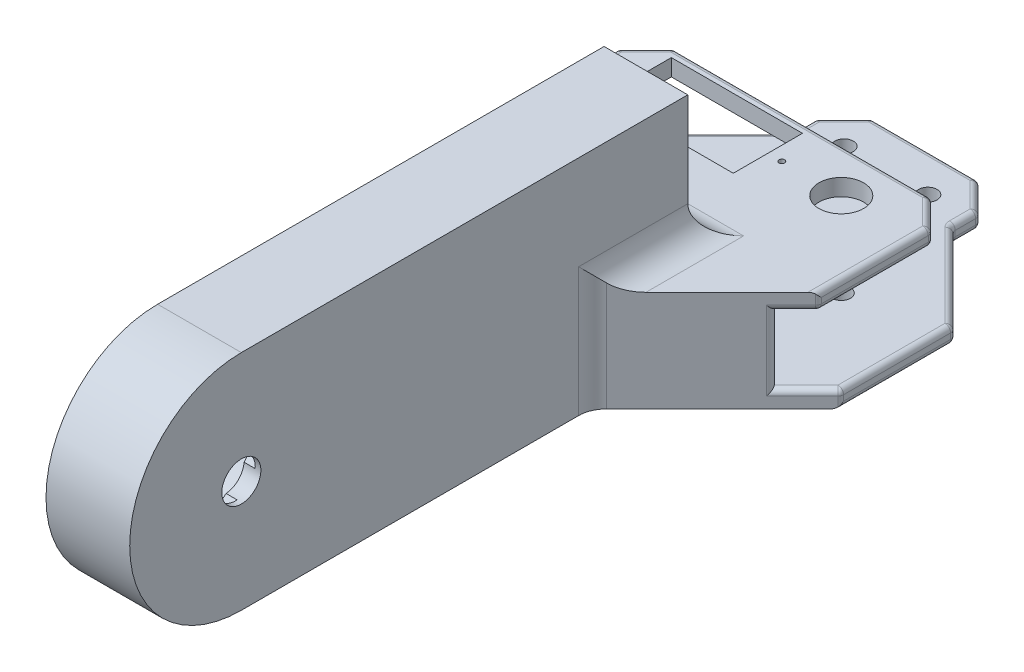
SolidWorks part; units mm, degrees
material "ABS"
ref_plane "Front Plane" through (0, 0, 0) normal (0, 0, 1) x (1, 0, 0)
ref_plane "Top Plane" through (0, 0, 0) normal (0, 1, 0) x (1, 0, 0)
ref_plane "Right Plane" through (0, 0, 0) normal (1, 0, 0) x (0, 0, -1)
sketch "Sketch1" plane through (0, 0, 0) normal (1, 0, 0) x (0, 0, -1)
  line L0 (0, 20) -> (80, 20)
  line L1 (0, -20) -> (80, -20)
  line L2 (80, 20) -> (80, -20)
  arc A0 (0, 20) -> (0, -20) centre (0, 0) ccw
  dimension "D1" = 40
  dimension "D2" = 80
  dimension "D3" = 80
extrude "Boss-Extrude1" add sketch "Sketch1" along normal blind 15
sketch "Sketch5" plane through (0, 0, 0) normal (-1, 0, 0) x (0, 0, 1)
  circle A0 centre (0, 0) radius 17
  arc A1 (0, -20) -> (0, 20) centre (0, 0) ccw construction
  dimension "D1" = 3
extrude "Cut-Extrude3" cut sketch "Sketch5" against normal offset from surface (12 mm away) 3 up to face at (15, 0, -35)
sketch "Sketch8" plane through (12, 0, 0) normal (-1, 0, 0) x (0, 0, 1)
  circle A0 centre (0, 0) radius 3.5
  dimension "D1" = 7
extrude "Cut-Extrude5" cut sketch "Sketch8" against normal up to surface (3 mm away) up to face at (15, 0, -35)
sketch "Sketch10" plane through (12, 0, 0) normal (-1, 0, 0) x (0, 0, 1)
  line L0 (-3.4905, -0.2571) -> (-11.7406, 8.915)
  line L1 (-8.915, 11.7406) -> (0.2571, 3.4905)
  line L2 (-2.4749, -2.4749) -> (2.4749, 2.4749) construction
  line L3 (0, -0.4614) -> (0, 0.843) construction
  line L6 (-10.253, 10.253) -> (2.4749, -2.4749) construction
  line L7 (11.7406, -8.915) -> (3.4905, 0.2571)
  line L8 (-0.2571, -3.4905) -> (8.915, -11.7406)
  arc A1 (-11.7406, 8.915) -> (-8.915, 11.7406) centre (-10.253, 10.253) cw
  circle A5 centre (0, 0) radius 3.5 construction
  arc A6 (-3.4885, -0.2839) -> (0.2571, 3.4905) centre (0, 0) cw
  arc A7 (-0.2839, -3.4885) -> (3.4905, 0.2571) centre (0, 0) ccw
  arc A8 (8.915, -11.7406) -> (11.7406, -8.915) centre (10.253, -10.253) ccw
  circle M6 centre (0, 0) radius 3.5
  dimension "D1" = 45
  dimension "D2" = 2.0008
  dimension "D5" = 90
  dimension "D3" = 5.3
  dimension "D4" = 18
extrude "Cut-Extrude8" cut sketch "Sketch10" against normal blind 2 contours A1 L0 L1 M6 | L8 A8 L7 M6
sketch "Sketch12" plane through (0, -20, 0) normal (0, -1, 0) x (1, 0, 0)
  line L0 (0, -80) -> (15, -80) construction
  line L1 (-17.5, -80) -> (32.5, -80)
  line L2 (32.5, -80) -> (37.5, -85)
  line L3 (37.5, -85) -> (37.5, -105)
  line L4 (37.5, -105) -> (22, -120.5)
  line L5 (22, -120.5) -> (22, -125)
  line L6 (22, -125) -> (17, -130)
  line L7 (17, -130) -> (-2, -130)
  line L8 (-2, -130) -> (-7, -125)
  line L9 (-7, -125) -> (-7, -120.5)
  line L10 (-7, -120.5) -> (-22.5, -105)
  line L12 (-22.5, -105) -> (-22.5, -85)
  line L13 (-22.5, -85) -> (-17.5, -80)
  line L14 (0, -80) -> (32.5, -80) construction
  line L15 (0, -70) -> (15, -70) construction
  line L16 (0, 0) -> (0, -80) construction
  line L17 (15, 0) -> (15, -80) construction
  line L18 (7.5, -80) -> (7.5, -70) construction
  line L19 (7.5, -130) -> (7.5, -80) construction
  line L20 (-22.5, -85) -> (37.5, -85) construction
  line L21 (-22.5, -105) -> (37.5, -105) construction
  line L22 (-7, -120.5) -> (22, -120.5) construction
  line L23 (-7, -125) -> (22, -125) construction
  dimension "D1" = 50
  dimension "D2" = 20
  dimension "D3" = 5
  dimension "D4" = 5
  dimension "D5" = 15.5
  dimension "D6" = 15.5
  dimension "D7" = 4.5
  dimension "D8" = 5
  dimension "D9" = 10
extrude "Boss-Extrude2" add sketch "Sketch12" against normal blind 3 separate body contours L12 L13 L1 L2 L3 L4 L5 L6 L7 L8 L9 L10
ref_plane "Plane1" through (0, -4.9, 0) normal (0, 1, 0) x (1, 0, 0)
sketch "Sketch13" plane through (0, -4.9, 0) normal (0, 1, 0) x (1, 0, 0)
  line L0 (-17.5, 80) -> (32.5, 80)
  line L1 (32.5, 80) -> (35.5, 83)
  line L3 (35.5, 83) -> (35.5, 103)
  line L4 (35.5, 103) -> (30.5, 108)
  line L5 (30.5, 108) -> (-15.5, 108)
  line L6 (-15.5, 108) -> (-20.5, 103)
  line L7 (-20.5, 103) -> (-20.5, 83)
  line L8 (-22.5, 85) -> (-17.5, 80) construction
  line L9 (-20.5, 83) -> (-17.5, 80)
  line L10 (-20.5, 83) -> (35.5, 83) construction
  line L11 (-20.5, 103) -> (35.5, 103) construction
  line L12 (7.5, 108) -> (7.5, 80) construction
  dimension "D1" = 3
  dimension "D2" = 20
  dimension "D3" = 5
extrude "Boss-Extrude3" add sketch "Sketch13" along normal blind 3
sketch "Sketch14" plane through (0, -20, 0) normal (0, -1, 0) x (1, 0, 0)
  line L0 (7.5, -123) -> (7.5, -130) construction
  line L1 (-7.5, -100) -> (22.5, -100) construction
  line L2 (17, -130) -> (-2, -130) construction
  line L3 (15, -123) -> (0, -123) construction
  line L4 (7.5, -123) -> (7.5, -100) construction
  circle A0 centre (-7.5, -100) radius 2
  circle A1 centre (22.5, -100) radius 1.65
  circle A2 centre (15, -123) radius 1.65
  circle A3 centre (0, -123) radius 1.65
  dimension "D1" = 4
  dimension "D6" = 3.3
  dimension "D2" = 15
  dimension "D3" = 7
  dimension "D4" = 30
  dimension "D5" = 23
extrude "Cut-Extrude10" cut sketch "Sketch14" against normal blind 3
sketch "Sketch15" plane through (0, -1.9, 0) normal (0, 1, 0) x (1, 0, 0)
  line L0 (30.5, 108) -> (-15.5, 108) construction
  line L1 (-14.15, 106.2) -> (9.35, 106.2)
  line L2 (-14.15, 106.2) -> (-14.15, 93.8)
  line L3 (-14.15, 93.8) -> (9.35, 93.8)
  line L4 (9.35, 106.2) -> (9.35, 93.8)
  line L5 (-14.15, 106.2) -> (9.35, 93.8) construction
  line L6 (-14.15, 93.8) -> (9.35, 106.2) construction
  line L7 (-20.5, 103) -> (-20.5, 83) construction
  line L8 (-16.65, 100) -> (-2.4, 100) construction
  line L9 (-2.4, 100) -> (11.85, 100) construction
  line L10 (11.85, 100) -> (22.5, 100) construction
  circle A0 centre (-16.65, 100) radius 0.5
  circle A1 centre (11.85, 100) radius 0.5
  circle A2 centre (22.5, 100) radius 4
  point P4 (-2.4, 100)
  dimension "D5" = 1
  dimension "D7" = 10.65
  dimension "D8" = 8
  dimension "D1" = 1.8
  dimension "D2" = 6.35
  dimension "D3" = 12.4
  dimension "D4" = 23.5
  dimension "D6" = 2.5
extrude "Cut-Extrude11" cut sketch "Sketch15" against normal blind 3
sketch "Sketch16" plane through (0, -1.9, 0) normal (0, 1, 0) x (1, 0, 0)
  line L0 (-17.5, 80) -> (0, 80)
  line L1 (0, 80) -> (0, 62.5)
  line L2 (0, 80) -> (0, 0) construction
  line L3 (0, 62.5) -> (-17.5, 80)
  line L4 (15, 80) -> (32.5, 80)
  line L5 (32.5, 80) -> (15, 62.5)
  line L6 (15, 80) -> (15, 0) construction
  line L7 (15, 62.5) -> (15, 80)
extrude "Boss-Extrude4" add sketch "Sketch16" against normal up to surface (18.1 mm away) up to face at (7.5, -20, -40)
fillet "Fillet2" radius 5 4 edges at (15, -10.95, -62.5) (15, -1.9, -71.25) (7.5, -1.9, -80) (0, -1.9, -71.25)
fillet "Fillet3" radius 1 50 edges at (22, -17, -122.75) (22, -20, -122.75) (-7, -17, -122.75) (-7, -20, -122.75) (-18, -4.9, -105.5) (-18, -1.9, -105.5) (-20.5, -3.4, -103) (-20.5, -4.9, -93) (-20.5, -1.9, -93) (-20.5, -3.4, -83) (7.5, -4.9, -108) (7.5, -1.9, -108) (-15.5, -3.4, -108) (33, -4.9, -105.5) (33, -1.9, -105.5) (30.5, -3.4, -108) (35.5, -3.4, -83) (35.5, -4.9, -93) (35.5, -1.9, -93) (35.5, -3.4, -103) (37.5, -18.5, -85) (37.5, -17, -95) (37.5, -20, -95) (22, -18.5, -125) (19.5, -17, -127.5) (19.5, -20, -127.5) (37.5, -18.5, -105) (29.75, -17, -112.75) (22, -18.5, -120.5) (29.75, -20, -112.75) (-22.5, -17, -95) (-22.5, -18.5, -85) (-22.5, -20, -95) (-4.5, -17, -127.5) (-7, -18.5, -125) (-4.5, -20, -127.5) (-7, -18.5, -120.5) (-14.75, -17, -112.75) (-22.5, -18.5, -105) (-14.75, -20, -112.75) (17, -18.5, -130) (7.5, -17, -130) (-2, -18.5, -130) (7.5, -20, -130) (34, -4.9, -81.5) (35, -17, -82.5) (-19, -4.9, -81.5) (-20, -17, -82.5) (32.5, -10.95, -80) (-17.5, -10.95, -80)
